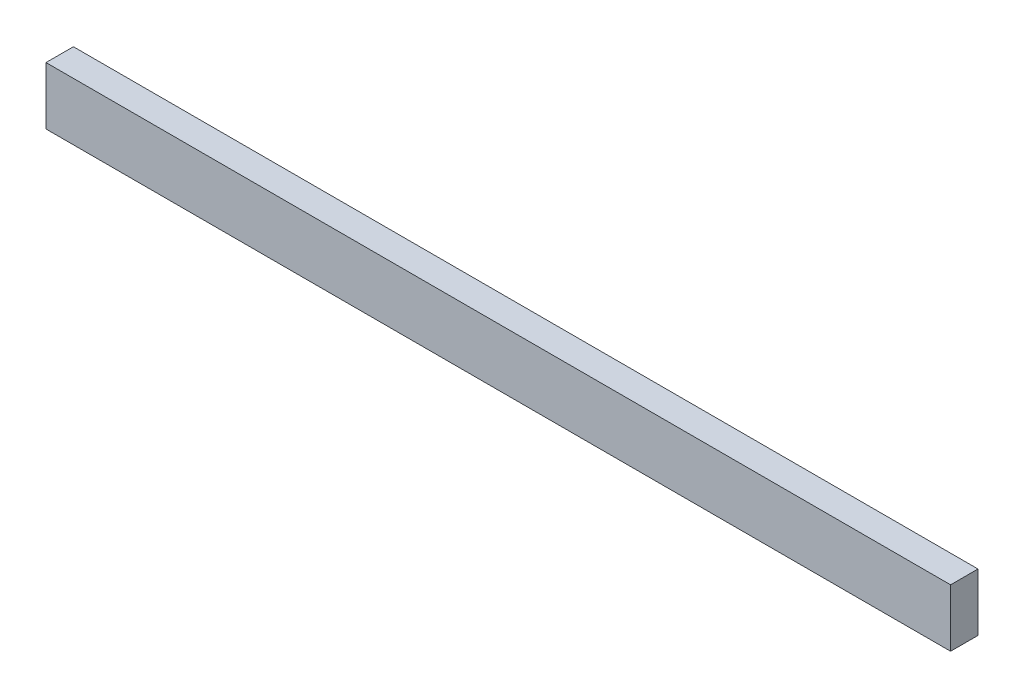
SolidWorks part; units mm, degrees
material "Free-Cutting Brass, UNS C36000"
ref_plane "Front Plane" through (0, 0, 0) normal (0, 0, 1) x (1, 0, 0)
ref_plane "Top Plane" through (0, 0, 0) normal (0, 1, 0) x (1, 0, 0)
ref_plane "Right Plane" through (0, 0, 0) normal (1, 0, 0) x (0, 0, -1)
sketch "Sketch1" plane through (0, 0, 0) normal (0, 0, 1) x (1, 0, 0)
  line L1 (0, 0) -> (41.91, 0)
  line L2 (0, 0) -> (0, 2.667)
  line L3 (0, 2.667) -> (41.91, 2.667)
  line L4 (41.91, 0) -> (41.91, 2.667)
  dimension "D1" = 41.91
  dimension "D2" = 2.667
extrude "Boss-Extrude1" add sketch "Sketch1" along normal blind 1.27
